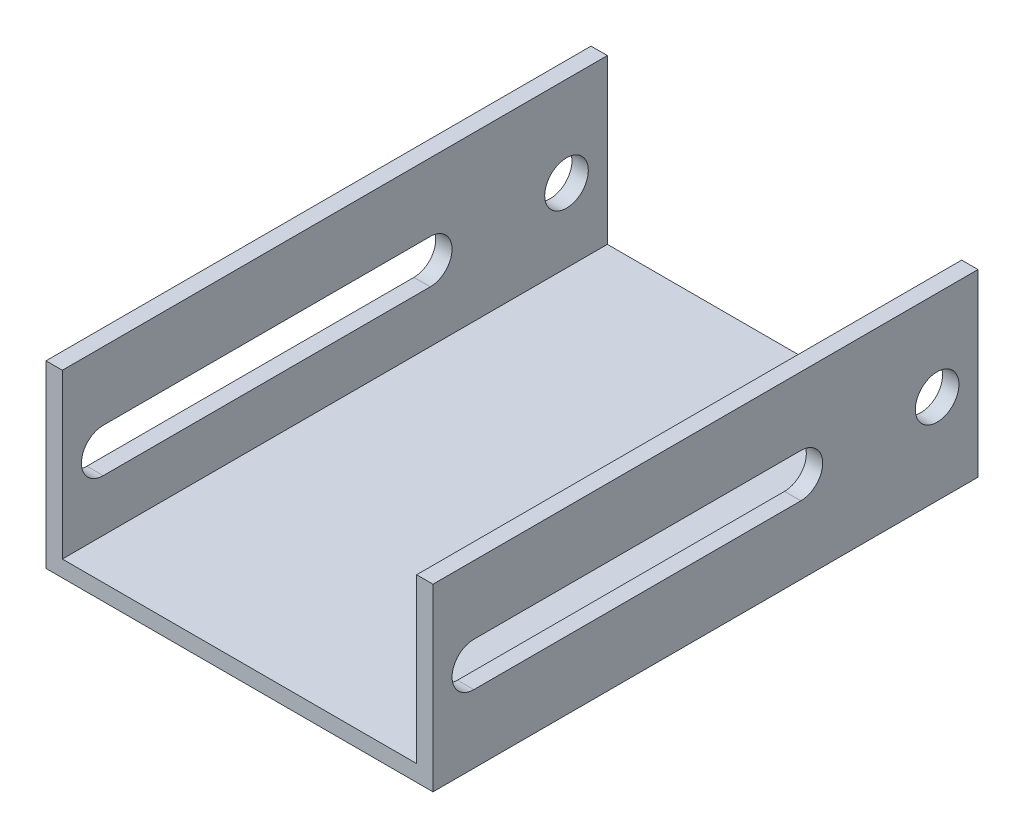
SolidWorks part; units mm, degrees
ref_plane "前视基准面" through (0, 0, 0) normal (0, 0, 1) x (1, 0, 0)
ref_plane "上视基准面" through (0, 0, 0) normal (0, 1, 0) x (1, 0, 0)
ref_plane "右视基准面" through (0, 0, 0) normal (1, 0, 0) x (0, 0, -1)
sketch "草图1" plane through (0, 0, 0) normal (0, 1, 0) x (1, 0, 0)
  line L1 (-35.5, -50) -> (35.5, -50)
  line L2 (-35.5, -50) -> (-35.5, 50)
  line L3 (-35.5, 50) -> (35.5, 50)
  line L4 (35.5, -50) -> (35.5, 50)
  line L5 (-35.5, -50) -> (35.5, 50) construction
  line L6 (-35.5, 50) -> (35.5, -50) construction
  point P0 (0, 0)
  dimension "D1" = 100
  dimension "D2" = 71
extrude "凸台-拉伸1" add sketch "草图1" along normal blind 3
sketch "草图2" plane through (0, 3, 0) normal (0, 1, 0) x (1, 0, 0)
  line L0 (-35.5, -50) -> (35.5, -50) construction
  line L1 (-35.5, 50) -> (-32.5, 50)
  line L2 (-35.5, 50) -> (-35.5, -50)
  line L3 (-35.5, -50) -> (-32.5, -50)
  line L4 (-32.5, 50) -> (-32.5, -50)
  line L5 (35.5, 50) -> (-35.5, 50) construction
  line L6 (35.5, -50) -> (32.5, -50)
  line L7 (35.5, -50) -> (35.5, 50)
  line L8 (35.5, 50) -> (32.5, 50)
  line L9 (32.5, -50) -> (32.5, 50)
  dimension "D1" = 3
  dimension "D2" = 3
extrude "凸台-拉伸2" add sketch "草图2" along normal blind 30
sketch "草图3" plane through (35.5, 0, 0) normal (1, 0, 0) x (0, 0, -1)
  line L0 (-50, 16.5) -> (50, 16.5) construction
  line L1 (-50, 33) -> (-50, 0) construction
  line L2 (50, 33) -> (50, 0) construction
  line L4 (-42.5, 12.5) -> (17.5, 12.5)
  line L5 (-42.5, 12.5) -> (-42.5, 20.5) construction
  line L6 (-42.5, 20.5) -> (17.5, 20.5)
  line L7 (17.5, 12.5) -> (17.5, 20.5) construction
  line L8 (-42.5, 12.5) -> (17.5, 20.5) construction
  line L9 (-42.5, 20.5) -> (17.5, 12.5) construction
  circle A0 centre (42.5, 16.5) radius 4
  arc A1 (17.5, 12.5) -> (17.5, 20.5) centre (17.5, 16.5) ccw
  arc A2 (-42.5, 20.5) -> (-42.5, 12.5) centre (-42.5, 16.5) ccw
  point P8 (-12.5, 16.5)
  point P17 (-42.7002, 10.5176)
  dimension "D1" = 8
  dimension "D2" = 4
  dimension "D3" = 60
  dimension "D4" = 85
  dimension "D5" = 7.5
extrude "切除-拉伸1" cut sketch "草图3" against normal up to surface (71 mm away) up to face at (-35.5, 16.5, 0)
